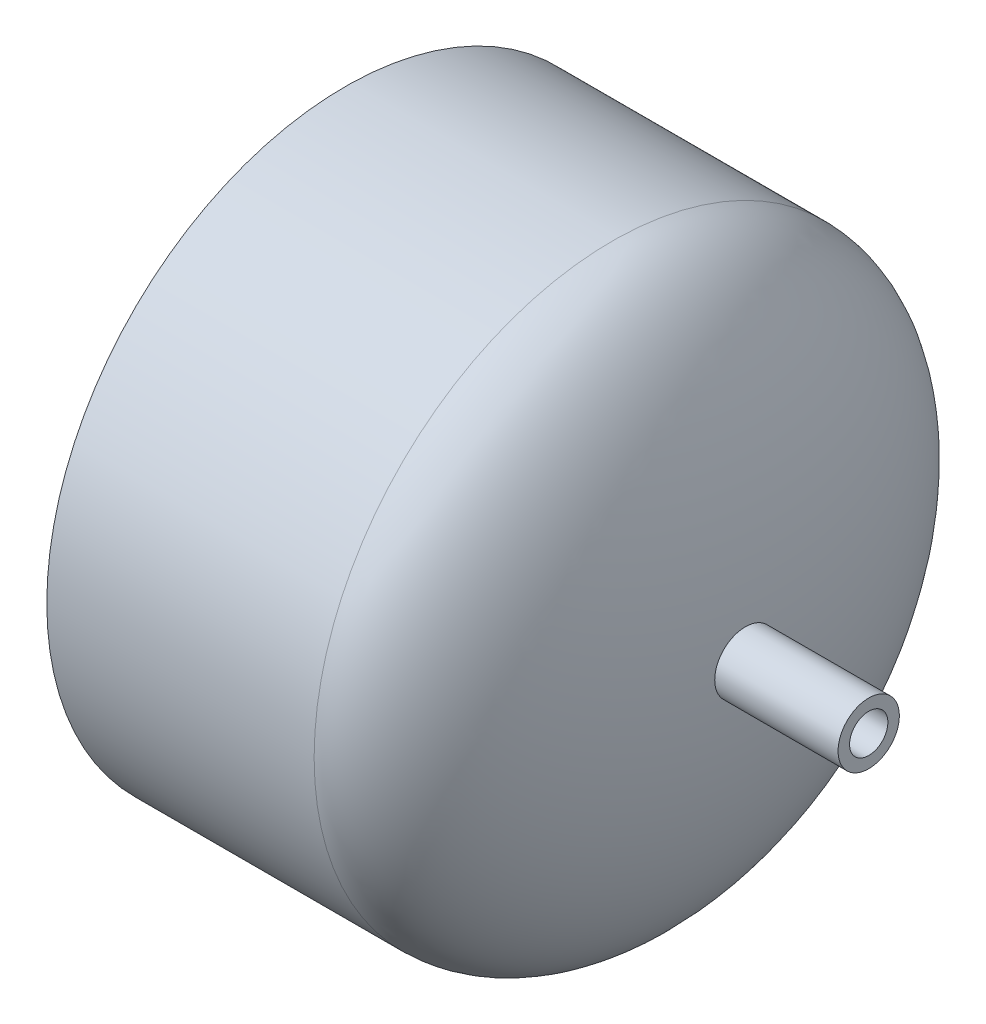
SolidWorks part; units mm, degrees
ref_plane "Front Plane" through (0, 0, 0) normal (0, 0, 1) x (1, 0, 0)
ref_plane "Top Plane" through (0, 0, 0) normal (0, 1, 0) x (1, 0, 0)
ref_plane "Right Plane" through (0, 0, 0) normal (1, 0, 0) x (0, 0, -1)
sketch "Sketch0" plane through (0, 0, 0) normal (0, 0, 1) x (1, 0, 0)
  line L0 (-166.116, 0) -> (0, 0) construction
  line L2 (-55.372, 0) -> (0, 0) construction
  line L4 (-166.116, 123.571) -> (-166.116, -123.571) construction
  line L5 (-55.372, 109.347) -> (-166.116, 109.9185) construction
  line L6 (-55.372, 109.347) -> (-55.372, -109.347) construction
  line L7 (-55.372, -109.347) -> (-166.116, -109.9185) construction
  line L8 (-166.116, 109.9185) -> (-166.116, -109.9185) construction
  line L14 (-55.372, 96.8375) -> (-55.372, -96.8375) construction
  dimension "M" = 247.142
  dimension "OD A" = 219.837
  dimension "OD B" = 218.694
  dimension "ID" = 193.675
  dimension "W" = 166.116
  dimension "C" = 110.744
sketch "Sketch1" plane through (0, 0, 0) normal (0, 0, 1) x (1, 0, 0)
  line L0 (-166.116, 0) -> (0, 0) construction
  line L1 (-166.116, 0) -> (0, 0) construction
  line L2 (-55.372, 0) -> (0, 0) construction
  line L3 (-166.116, -123.571) -> (-55.372, -123.571)
  line L4 (-166.116, -123.571) -> (-166.116, -109.9185)
  line L5 (-166.116, -109.9185) -> (-55.372, -109.347)
  line L6 (-55.372, 0) -> (-55.372, -109.347) construction
  line L7 (-55.372, -109.347) -> (-55.372, -123.571) construction
  line L8 (-14.224, 0) -> (0, 0)
  ellipse E0 centre (-55.372, 0) end of major axis (-55.372, 123.571) minor radius 55.372 (-55.372, -123.571) -> (0, 0) ccw
  ellipse E1 centre (-55.372, 0) end of major axis (-55.372, -109.347) minor radius 41.148 (-55.372, -109.347) -> (-14.224, 0) ccw
revolve "Revolve1" add sketch "Sketch1" angle 360 about L1
ref_plane "Plane1" through (0, 0, 0) normal (1, 0, 0) x (0, 0, -1)
sketch "Sketch2" plane through (0, 0, 0) normal (1, 0, 0) x (0, 0, -1)
  circle A0 centre (0, 0) radius 12.7
  circle A1 centre (0, 0) radius 7.9375
  dimension "D1" = 25.4
  dimension "D2" = 15.875
extrude "Boss-Extrude1" add sketch "Sketch2" along normal blind 50.8 and the other way blind 3.556
